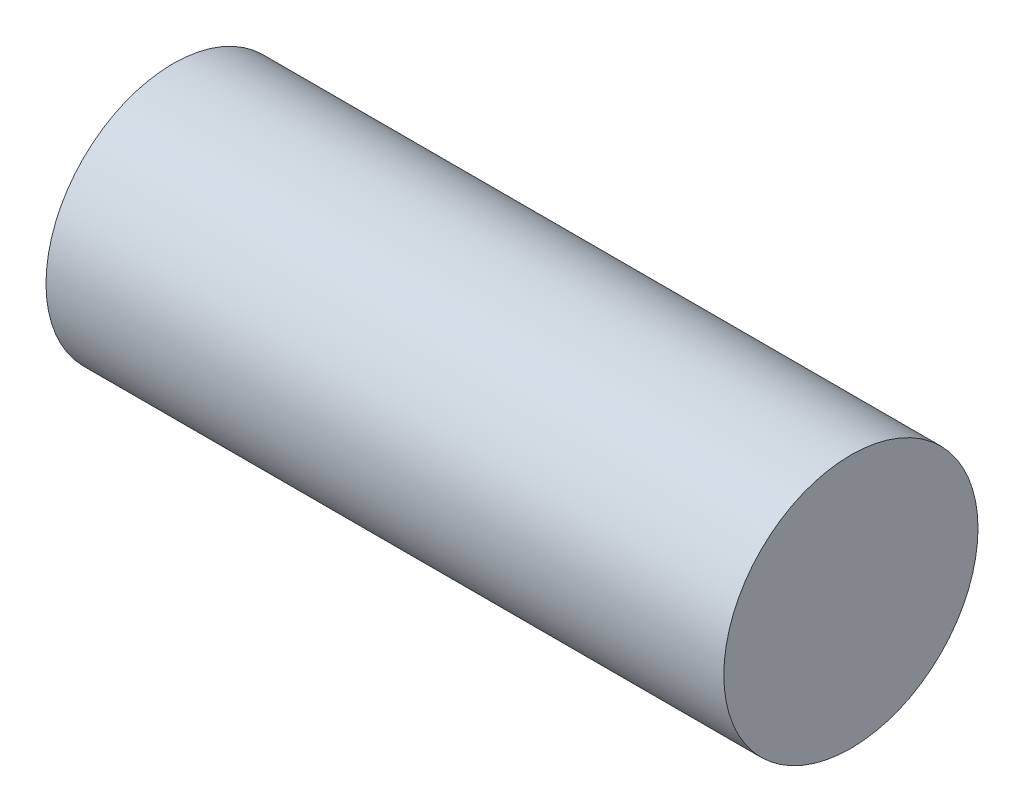
SolidWorks part; units mm, degrees
ref_plane "Front Plane" through (0, 0, 0) normal (0, 0, 1) x (1, 0, 0)
ref_plane "Top Plane" through (0, 0, 0) normal (0, 1, 0) x (1, 0, 0)
ref_plane "Right Plane" through (0, 0, 0) normal (1, 0, 0) x (0, 0, -1)
sketch "Sketch1" plane through (0, 0, 0) normal (1, 0, 0) x (0, 0, -1)
  circle A0 centre (0, 0) radius 9.525
extrude "Boss-Extrude1" add sketch "Sketch1" along normal blind 50.8 contours A0
